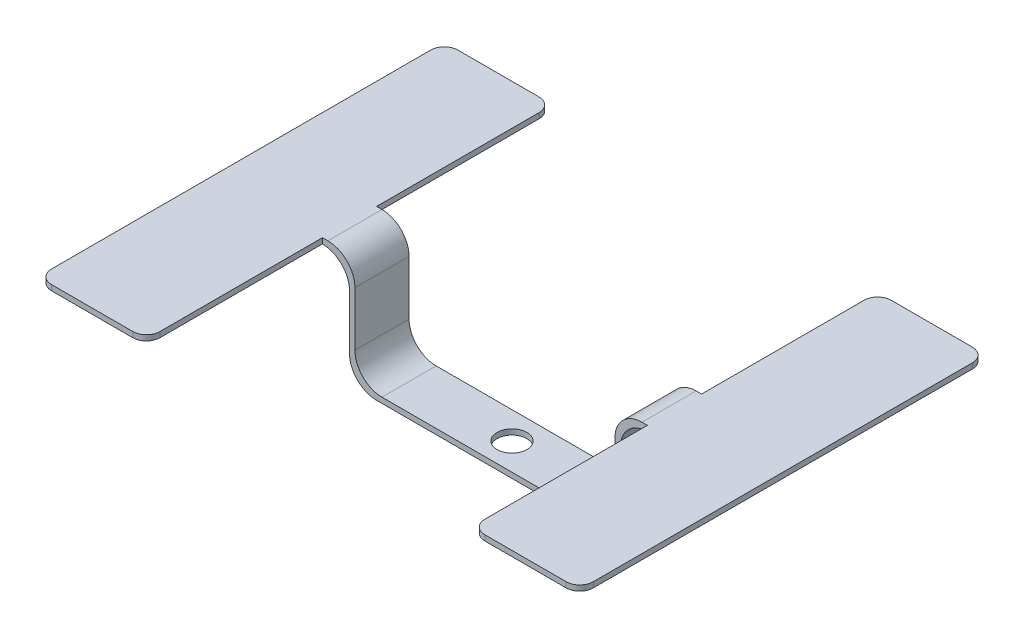
SolidWorks part; units mm, degrees
ref_plane "Front" through (0, 0, 0) normal (0, 0, 1) x (1, 0, 0)
ref_plane "Top" through (0, 0, 0) normal (0, 1, 0) x (1, 0, 0)
ref_plane "Right" through (0, 0, 0) normal (1, 0, 0) x (0, 0, -1)
sketch "Sketch1" plane through (0, 0, 0) normal (0, 0, 1) x (1, 0, 0)
  line L0 (0, 0) -> (-50, 0)
  line L1 (-50, 0) -> (-50, -40)
  line L2 (-50, -40) -> (-100, -40)
  line L3 (0, 2) -> (-52, 2)
  line L4 (-52, 2) -> (-52, -38)
  line L5 (-52, -38) -> (-100, -38)
  line L6 (-100, -38) -> (-100, -40)
  line L7 (0, 2) -> (0, 0)
  dimension "D1" = 50
  dimension "D2" = 40
  dimension "D3" = 50
  dimension "D4" = 2
extrude "Boss-Extrude1" add sketch "Sketch1" along normal mid plane 20
fillet "Fillet1" radius 10 4 edges at (-50, -40, 0) (-52, -38, 0) (-52, 2, 0) (-50, 0, 0)
sketch "Sketch2" plane through (0, 0, 0) normal (0, 0, 1) x (1, 0, 0)
  line L0 (-40, 0) -> (0, 0) construction
  line L1 (0, 0) -> (0, 2) construction
  line L2 (0, 2) -> (-42, 2) construction
  line L3 (-40, 0) -> (0, 0)
  line L4 (0, 0) -> (0, 2)
  line L5 (0, 2) -> (-40, 2)
  line L6 (-40, 0) -> (-40, 2)
extrude "Boss-Extrude2" add sketch "Sketch2" along normal mid plane 150
fillet "Fillet2" radius 5 4 edges at (0, 1, -75) (-40, 1, -75) (-40, 1, 75) (0, 1, 75)
mirror "Mirror1" about plane through (-100, -38, 10) normal (1, 0, 0) of bodies 102
sketch "Sketch4" plane through (0, -40, 0) normal (0, -1, 0) x (1, 0, 0)
  line L0 (-140, 0) -> (-60, 0) construction
  line L1 (-140, -10) -> (-140, 10) construction
  line L2 (-60, -10) -> (-60, 10) construction
  circle A0 centre (-100, 0) radius 5.5
  dimension "D1" = 11
extrude "Cut-Extrude1" cut sketch "Sketch4" against normal up to next
